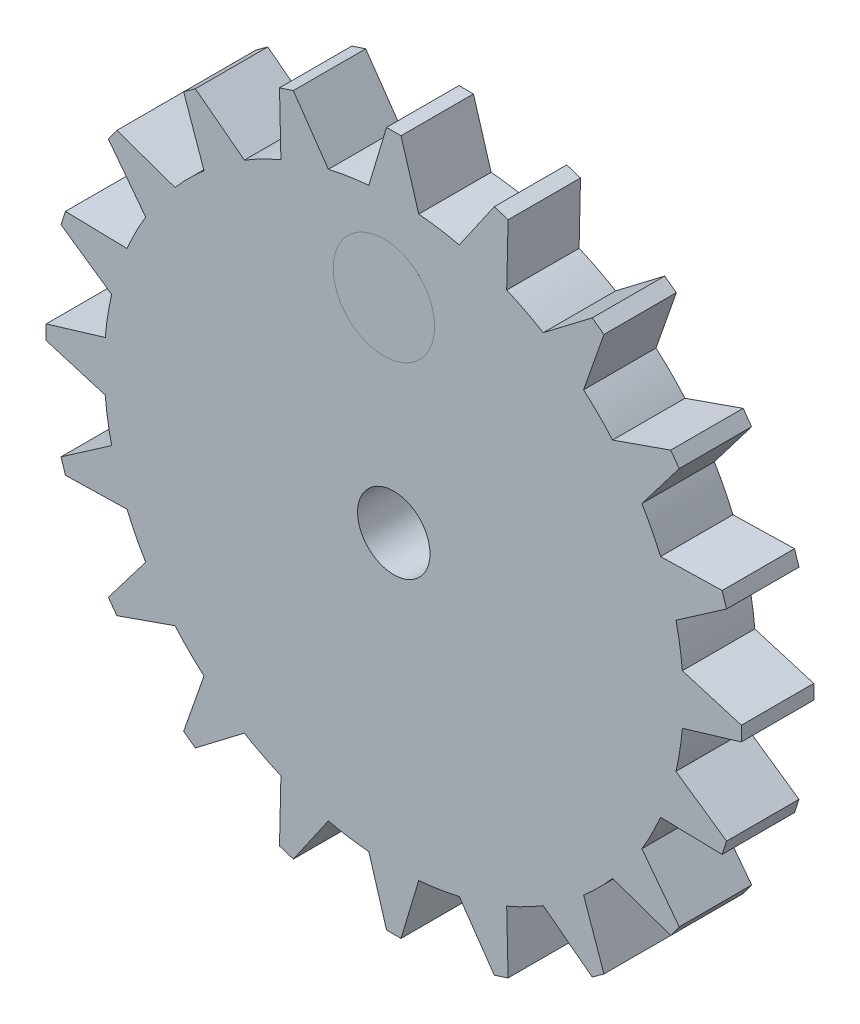
SolidWorks part; units mm, degrees
ref_plane "Front Plane" through (0, 0, 0) normal (0, 0, 1) x (1, 0, 0)
ref_plane "Top Plane" through (0, 0, 0) normal (0, 1, 0) x (1, 0, 0)
ref_plane "Right Plane" through (0, 0, 0) normal (1, 0, 0) x (0, 0, -1)
sketch "Sketch1" plane through (0, 0, 0) normal (0, 0, 1) x (1, 0, 0)
  circle A0 centre (0, 0) radius 40
  dimension "D1" = 80
extrude "Boss-Extrude1" add sketch "Sketch1" along normal blind 10
sketch "Sketch2" plane through (0, 0, 10) normal (0, 0, 1) x (1, 0, 0)
  circle A0 centre (0, 0) radius 5
  dimension "D1" = 10
extrude "Cut-Extrude1" cut sketch "Sketch2" against normal blind 10
sketch "Sketch3" plane through (0, 0, 10) normal (0, 0, 1) x (1, 0, 0)
  line L0 (0, 0) -> (0, 40) construction
  line L1 (0, 40) -> (0, 48) construction
  line L2 (-1, 48) -> (1, 48)
  line L3 (1, 48) -> (4, 38)
  line L4 (4, 38) -> (-4, 38)
  line L5 (-4, 38) -> (-1, 48)
  line L6 (0, 40) -> (0, 38) construction
  line L7 (7.9384, 37.3762) -> (13.8818, 45.9597)
  line L8 (13.8818, 45.9597) -> (15.7839, 45.3417)
  line L9 (15.7839, 45.3417) -> (15.5469, 34.9041)
  line L10 (15.5469, 34.9041) -> (7.9384, 37.3762)
  line L11 (19.0998, 33.0938) -> (27.4047, 39.4206)
  line L12 (27.4047, 39.4206) -> (29.0227, 38.245)
  line L13 (29.0227, 38.245) -> (25.5719, 28.3915)
  line L14 (25.5719, 28.3915) -> (19.0998, 33.0938)
  line L15 (28.3915, 25.5719) -> (38.245, 29.0227)
  line L16 (38.245, 29.0227) -> (39.4206, 27.4047)
  line L17 (39.4206, 27.4047) -> (33.0938, 19.0998)
  line L18 (33.0938, 19.0998) -> (28.3915, 25.5719)
  line L19 (34.9041, 15.5469) -> (45.3417, 15.7839)
  line L20 (45.3417, 15.7839) -> (45.9597, 13.8818)
  line L21 (45.9597, 13.8818) -> (37.3762, 7.9384)
  line L22 (37.3762, 7.9384) -> (34.9041, 15.5469)
  line L23 (38, 4) -> (48, 1)
  line L24 (48, 1) -> (48, -1)
  line L25 (48, -1) -> (38, -4)
  line L26 (38, -4) -> (38, 4)
  line L27 (37.3762, -7.9384) -> (45.9597, -13.8818)
  line L28 (45.9597, -13.8818) -> (45.3417, -15.7839)
  line L29 (45.3417, -15.7839) -> (34.9041, -15.5469)
  line L30 (34.9041, -15.5469) -> (37.3762, -7.9384)
  line L31 (33.0938, -19.0998) -> (39.4206, -27.4047)
  line L32 (39.4206, -27.4047) -> (38.245, -29.0227)
  line L33 (38.245, -29.0227) -> (28.3915, -25.5719)
  line L34 (28.3915, -25.5719) -> (33.0938, -19.0998)
  line L35 (25.5719, -28.3915) -> (29.0227, -38.245)
  line L36 (29.0227, -38.245) -> (27.4047, -39.4206)
  line L37 (27.4047, -39.4206) -> (19.0998, -33.0938)
  line L38 (19.0998, -33.0938) -> (25.5719, -28.3915)
  line L39 (15.5469, -34.9041) -> (15.7839, -45.3417)
  line L40 (15.7839, -45.3417) -> (13.8818, -45.9597)
  line L41 (13.8818, -45.9597) -> (7.9384, -37.3762)
  line L42 (7.9384, -37.3762) -> (15.5469, -34.9041)
  line L43 (4, -38) -> (1, -48)
  line L44 (1, -48) -> (-1, -48)
  line L45 (-1, -48) -> (-4, -38)
  line L46 (-4, -38) -> (4, -38)
  line L47 (-7.9384, -37.3762) -> (-13.8818, -45.9597)
  line L48 (-13.8818, -45.9597) -> (-15.7839, -45.3417)
  line L49 (-15.7839, -45.3417) -> (-15.5469, -34.9041)
  line L50 (-15.5469, -34.9041) -> (-7.9384, -37.3762)
  line L51 (-19.0998, -33.0938) -> (-27.4047, -39.4206)
  line L52 (-27.4047, -39.4206) -> (-29.0227, -38.245)
  line L53 (-29.0227, -38.245) -> (-25.5719, -28.3915)
  line L54 (-25.5719, -28.3915) -> (-19.0998, -33.0938)
  line L55 (-28.3915, -25.5719) -> (-38.245, -29.0227)
  line L56 (-38.245, -29.0227) -> (-39.4206, -27.4047)
  line L57 (-39.4206, -27.4047) -> (-33.0938, -19.0998)
  line L58 (-33.0938, -19.0998) -> (-28.3915, -25.5719)
  line L59 (-34.9041, -15.5469) -> (-45.3417, -15.7839)
  line L60 (-45.3417, -15.7839) -> (-45.9597, -13.8818)
  line L61 (-45.9597, -13.8818) -> (-37.3762, -7.9384)
  line L62 (-37.3762, -7.9384) -> (-34.9041, -15.5469)
  line L63 (-38, -4) -> (-48, -1)
  line L64 (-48, -1) -> (-48, 1)
  line L65 (-48, 1) -> (-38, 4)
  line L66 (-38, 4) -> (-38, -4)
  line L67 (-37.3762, 7.9384) -> (-45.9597, 13.8818)
  line L68 (-45.9597, 13.8818) -> (-45.3417, 15.7839)
  line L69 (-45.3417, 15.7839) -> (-34.9041, 15.5469)
  line L70 (-34.9041, 15.5469) -> (-37.3762, 7.9384)
  line L71 (-33.0938, 19.0998) -> (-39.4206, 27.4047)
  line L72 (-39.4206, 27.4047) -> (-38.245, 29.0227)
  line L73 (-38.245, 29.0227) -> (-28.3915, 25.5719)
  line L74 (-28.3915, 25.5719) -> (-33.0938, 19.0998)
  line L75 (-25.5719, 28.3915) -> (-29.0227, 38.245)
  line L76 (-29.0227, 38.245) -> (-27.4047, 39.4206)
  line L77 (-27.4047, 39.4206) -> (-19.0998, 33.0938)
  line L78 (-19.0998, 33.0938) -> (-25.5719, 28.3915)
  line L79 (-15.5469, 34.9041) -> (-15.7839, 45.3417)
  line L80 (-15.7839, 45.3417) -> (-13.8818, 45.9597)
  line L81 (-13.8818, 45.9597) -> (-7.9384, 37.3762)
  line L82 (-7.9384, 37.3762) -> (-15.5469, 34.9041)
  circle A0 centre (0, 0) radius 40 construction
  point P11 (0, 48)
  point P93 (0, 0)
  dimension "D1" = 2
  dimension "D2" = 2
  dimension "D3" = 8
  dimension "D4" = 8
  dimension "D5" = 20
extrude "Boss-Extrude2" add sketch "Sketch3" against normal blind 10
sketch "Sketch4" plane through (0, 0, 10) normal (0, 0, 1) x (1, 0, 0)
  circle A0 centre (-1.3669, 27.4738) radius 5
  dimension "D1" = 10
extrude "Boss-Extrude3" add sketch "Sketch4" along normal blind 0.0001
sketch "Sketch5" plane through (0, 0, 10) normal (0, 0, 1) x (1, 0, 0)
  circle A0 centre (-1.3669, 27.4738) radius 7
  dimension "D1" = 14
extrude "Boss-Extrude4" add sketch "Sketch5" along normal blind 0.0001
sketch "Sketch6" plane through (0, 0, 0) normal (0, 0, -1) x (-1, 0, 0)
  circle A0 centre (0, 0) radius 15
  dimension "D1" = 30
extrude "Boss-Extrude5" add sketch "Sketch6" along normal blind 3
sketch "Sketch7" plane through (0, 0, -3) normal (0, 0, -1) x (-1, 0, 0)
  circle A0 centre (0, 0) radius 5
  dimension "D1" = 10
extrude "Cut-Extrude2" cut sketch "Sketch7" against normal blind 3
